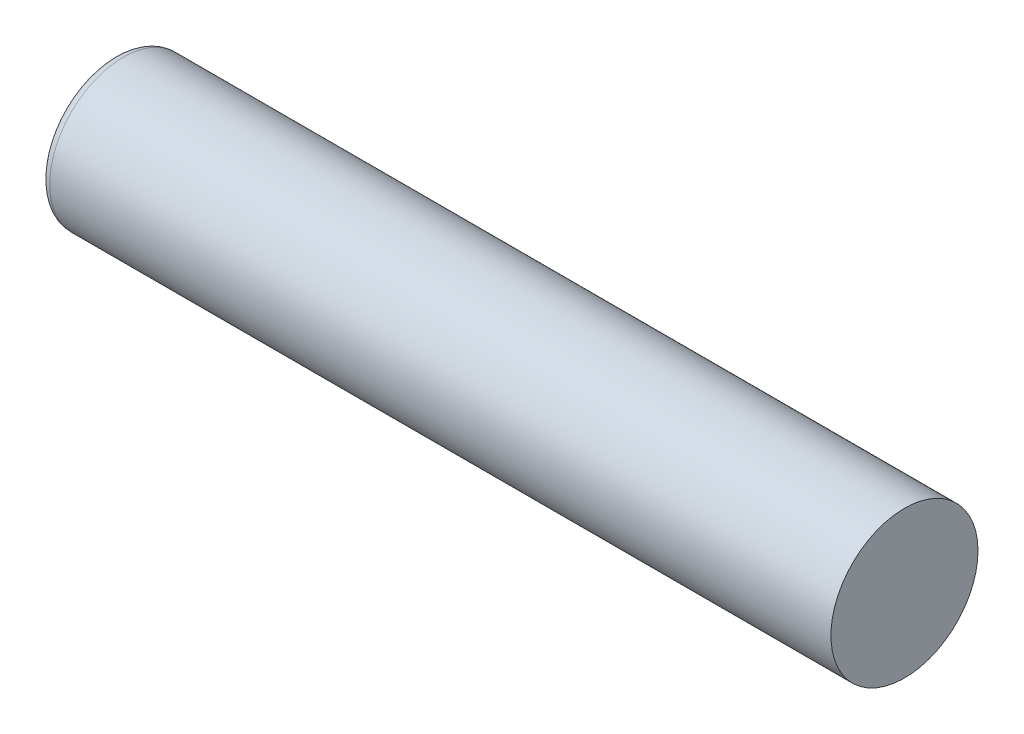
SolidWorks part; units mm, degrees
ref_plane "Alzado" through (0, 0, 0) normal (0, 0, 1) x (1, 0, 0)
ref_plane "Planta" through (0, 0, 0) normal (0, 1, 0) x (1, 0, 0)
ref_plane "Vista lateral" through (0, 0, 0) normal (1, 0, 0) x (0, 0, -1)
sketch "Croquis5" plane through (0, 0, 0) normal (1, 0, 0) x (0, 0, -1)
  circle A0 centre (0, 0) radius 4
  dimension "D1" = 8
extrude "Saliente-Extruir2" add sketch "Croquis5" along normal blind 3 contours A0
sketch "Croquis6" plane through (3, 0, 0) normal (1, 0, 0) x (0, 0, -1)
  circle A0 centre (0, 0) radius 4
  dimension "D1" = 8
extrude "Saliente-Extruir3" add sketch "Croquis6" along normal blind 40
fillet "Redondeo1" radius 0.5 1 edges at (0, 0, -4)
